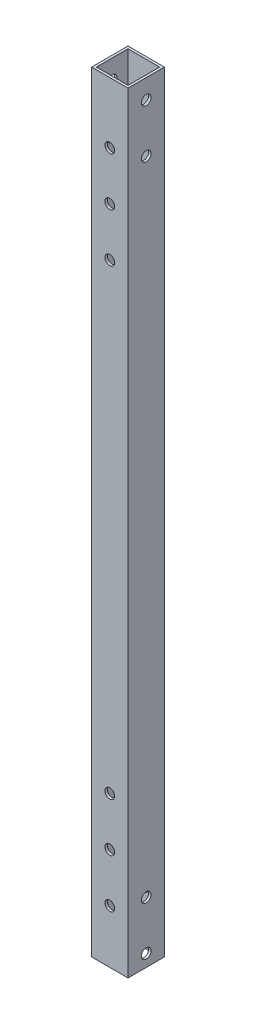
SolidWorks part; units mm, degrees
material "6061 合金"
ref_plane "Front" through (0, 0, 0) normal (0, 0, 1) x (1, 0, 0)
ref_plane "Top" through (0, 0, 0) normal (0, 1, 0) x (1, 0, 0)
ref_plane "Right" through (0, 0, 0) normal (1, 0, 0) x (0, 0, -1)
sketch "草图1" plane through (0, 0, 0) normal (0, 1, 0) x (1, 0, 0)
  line L1 (-7.5, -7.5) -> (7.5, -7.5)
  line L2 (-7.5, -7.5) -> (-7.5, 7.5)
  line L3 (-7.5, 7.5) -> (7.5, 7.5)
  line L4 (7.5, -7.5) -> (7.5, 7.5)
  line L5 (-7.5, -7.5) -> (7.5, 7.5) construction
  line L6 (-7.5, 7.5) -> (7.5, -7.5) construction
  line L7 (-6.5, -6.5) -> (6.5, -6.5)
  line L8 (-6.5, -6.5) -> (-6.5, 6.5)
  line L9 (-6.5, 6.5) -> (6.5, 6.5)
  line L10 (6.5, -6.5) -> (6.5, 6.5)
  line L11 (-6.5, -6.5) -> (6.5, 6.5) construction
  line L12 (-6.5, 6.5) -> (6.5, -6.5) construction
  point P0 (0, 0)
  point P5 (0, 0)
  dimension "D1" = 15
  dimension "D2" = 15
  dimension "D3" = 1
  dimension "D4" = 1
extrude "凸台-拉伸1" add sketch "草图1" along normal blind 320
sketch "草图3" plane through (0, 0, 7.5) normal (0, 0, 1) x (1, 0, 0)
  line L0 (0, 50) -> (0, -49950) construction
  line L1 (-7.5, 320) -> (7.5, 320) construction
  line L2 (5, 160) -> (-49995, 160) construction
  line L3 (7.5, 320) -> (7.5, 0) construction
  circle A0 centre (0, 295) radius 2
  circle A1 centre (0, 275) radius 2
  circle A2 centre (0, 45) radius 2
  circle A3 centre (0, 25) radius 2
  circle A4 centre (0, 255) radius 2
  circle A5 centre (0, 65) radius 2
  point P4 (0, 320)
  point P13 (7.5, 160)
  dimension "D1" = 4
  dimension "D2" = 4
  dimension "D5" = 4
  dimension "D3" = 20
  dimension "D4" = 25
  dimension "D6" = 20
extrude "切除-拉伸2" cut sketch "草图3" against normal through all
sketch "草图4" plane through (-7.5, 0, 0) normal (-1, 0, 0) x (0, 0, 1)
  line L0 (0, 0) -> (0, 50000) construction
  line L1 (-7.5, 0) -> (7.5, 0) construction
  line L2 (-7.5, 160) -> (49992.5, 160) construction
  line L3 (-7.5, 320) -> (-7.5, 0) construction
  line L4 (7.5, 320) -> (7.5, 0) construction
  circle A0 centre (0, 8) radius 2
  circle A1 centre (0, 28) radius 2
  circle A2 centre (0, 292) radius 2
  circle A3 centre (0, 312) radius 2
  point P13 (-7.5, 160)
  point P16 (7.5, 160)
  dimension "D1" = 4
  dimension "D2" = 4
  dimension "D3" = 8
  dimension "D4" = 20
extrude "切除-拉伸3" cut sketch "草图4" against normal through all
sketch "草图5" [suppressed] plane through (7.5, 0, 0) normal (1, 0, 0) x (0, 0, -1)
  circle A0 centre (0, 11) radius 2 construction
  circle A1 centre (0, 41) radius 2 construction
  circle A2 centre (0, 259) radius 2 construction
  circle A3 centre (0, 289) radius 2 construction
  circle A4 centre (0, 11) radius 2
  circle A5 centre (0, 41) radius 2
  circle A6 centre (0, 259) radius 2
  circle A7 centre (0, 289) radius 2
extrude "凸台-拉伸2" [suppressed] add sketch "草图5" against normal blind 1
ref_plane "基准面1" [suppressed] through (0, 0, 0) normal (-1, 0, 0) x (0, 0, 1)
mirror "镜向1" [suppressed] about plane through (0, 0, 0) normal (-1, 0, 0)
sketch "草图6" [suppressed] plane through (-7.5, 0, 0) normal (-1, 0, 0) x (0, 0, 1)
  line L0 (-7.5, 0) -> (7.5, 0) construction
  line L1 (7.5, 150) -> (-78.7867, 150) construction
  line L2 (7.5, 300) -> (7.5, 0) construction
  circle A0 centre (0, 16) radius 1.65
  circle A1 centre (0, 36) radius 1.65
  circle A2 centre (0, 284) radius 1.65
  circle A3 centre (0, 264) radius 1.65
  dimension "D1" = 20
  dimension "D2" = 16
  dimension "D3" = 3.3
extrude "切除-拉伸4" [suppressed] cut sketch "草图6" against normal through all
sketch "草图7" plane through (7.5, 0, 0) normal (1, 0, 0) x (0, 0, -1)
  line L0 (7.5, 320) -> (7.5, 0) construction
  line L1 (-7.5, 0) -> (7.5, 0)
  line L2 (-7.5, 0) -> (-7.5, 3)
  line L3 (-7.5, 3) -> (7.5, 3)
  line L4 (7.5, 0) -> (7.5, 3)
  dimension "D1" = 3
extrude "切除-拉伸6" cut sketch "草图7" against normal blind 20
equation "\"3。3\"=3.01309"
